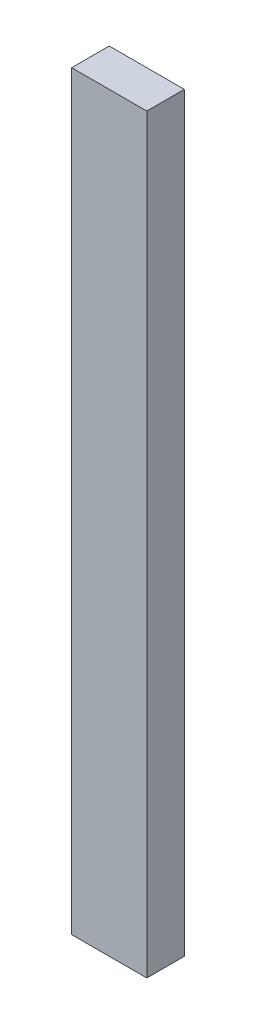
SolidWorks part; units mm, degrees
ref_plane "Спереди" through (0, 0, 0) normal (0, 0, 1) x (1, 0, 0)
ref_plane "Сверху" through (0, 0, 0) normal (0, 1, 0) x (1, 0, 0)
ref_plane "Справа" through (0, 0, 0) normal (1, 0, 0) x (0, 0, -1)
sketch "Эскиз1" plane through (0, 0, 0) normal (0, 1, 0) x (1, 0, 0)
  line L1 (0, 0) -> (40, 0)
  line L2 (0, 0) -> (0, 20)
  line L3 (0, 20) -> (40, 20)
  line L4 (40, 0) -> (40, 20)
  dimension "D1" = 20
  dimension "D2" = 40
extrude "Бобышка-Вытянуть1" add sketch "Эскиз1" along normal blind 400
